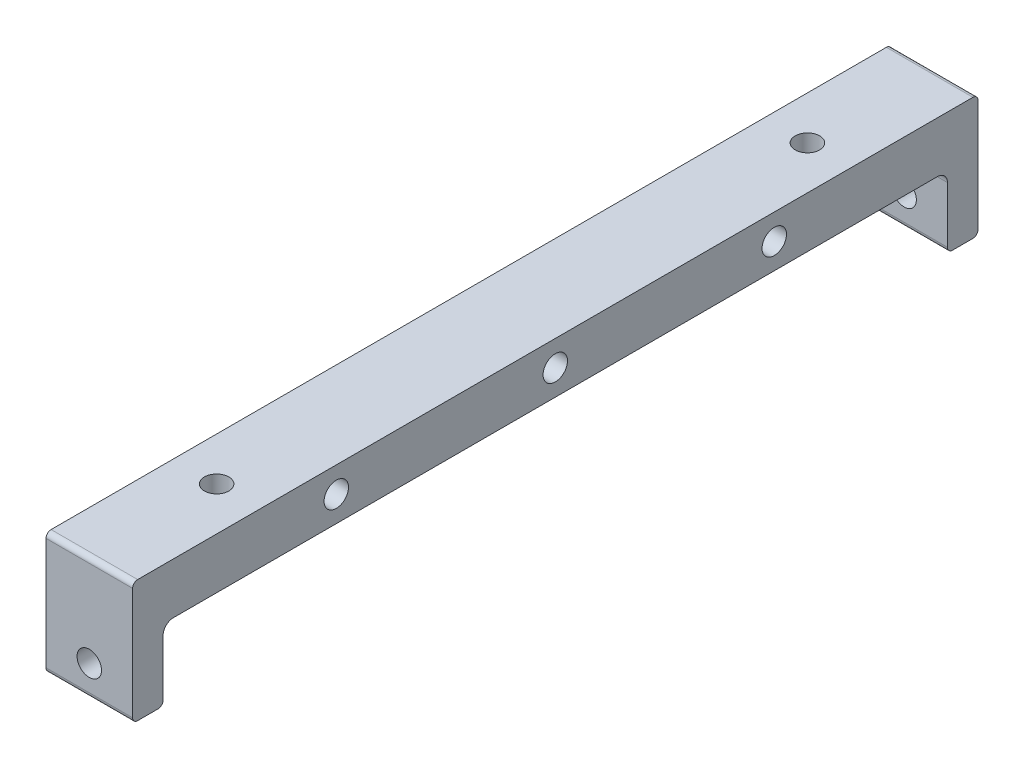
SolidWorks part; units mm, degrees
material "6061 Alloy"
ref_plane "Frontal" through (0, 0, 0) normal (0, 0, 1) x (1, 0, 0)
ref_plane "Superior" through (0, 0, 0) normal (0, 1, 0) x (1, 0, 0)
ref_plane "Direito" through (0, 0, 0) normal (1, 0, 0) x (0, 0, -1)
sketch "Sketch1" plane through (0, 0, 0) normal (0, 0, 1) x (1, 0, 0)
  line L1 (-4.25, -6) -> (4.25, -6)
  line L2 (-4.25, -6) -> (-4.25, 6)
  line L3 (-4.25, 6) -> (4.25, 6)
  line L4 (4.25, -6) -> (4.25, 6)
  line L5 (-4.25, -6) -> (4.25, 6) construction
  line L6 (-4.25, 6) -> (4.25, -6) construction
  point P0 (0, 0)
  dimension "D1" = 8.5
  dimension "D2" = 12
extrude "Boss-Extrude1" add sketch "Sketch1" along normal mid plane 83
sketch "Sketch2" plane through (4.25, 0, 0) normal (1, 0, 0) x (0, 0, -1)
  line L0 (-37.5, 1) -> (37.5, 1)
  line L1 (38.5, 0) -> (38.5, -6)
  line L2 (-41.5, -6) -> (41.5, -6) construction
  line L3 (38.5, -6) -> (-38.5, -6)
  line L4 (-38.5, -6) -> (-38.5, 0)
  line L5 (-41.5, 6) -> (41.5, 6) construction
  line L6 (-41.5, -6) -> (-41.5, 6) construction
  line L7 (41.5, -6) -> (41.5, 6) construction
  arc A0 (37.5, 1) -> (38.5, 0) centre (37.5, 0) cw
  arc A1 (-37.5, 1) -> (-38.5, 0) centre (-37.5, 0) ccw
  dimension "D4" = 1
  dimension "D5" = 1
  dimension "D1" = 5
  dimension "D2" = 3
  dimension "D3" = 3
extrude "Cut-Extrude1" cut sketch "Sketch2" against normal through all
fillet "Fillet1" radius 0.5 6 edges at (0, -6, 38.5) (0, -6, 41.5) (0, -6, -38.5) (0, -6, -41.5) (0, 6, 41.5) (0, 6, -41.5)
hole_wizard "M2 Hole1-R" positions "Sketch19" profile "Sketch18" hole size "M2" standard "DIN"
sketch "Sketch19" plane through (4.25, 0, 0) normal (1, 0, 0) x (0, 0, -1)
  line L0 (-41.5, -5.5) -> (-41.5, 5.5) construction
  line L1 (41.5, -5.5) -> (41.5, 5.5) construction
  line L2 (-41, 6) -> (41, 6) construction
  point P0 (21.5, 3.5)
  point P2 (-21.5, 3.5)
  dimension "D1" = 20
  dimension "D2" = 20
  dimension "D3" = 2.5
sketch "Sketch18" plane through (4.25, 3.5, -21.5) normal (0, 1, 0) x (0, 0, -1)
  line L0 (0, 0) -> (0, 5.721)
  line L1 (0, 5.721) -> (1.2, 5)
  line L2 (1.2, 5) -> (1.2, 0)
  line L5 (1.2, 0) -> (0, 0)
  line L10 (0, 5.721) -> (-1.2, 5) construction
  line L11 (0, -6.35) -> (0, 107.95) construction
  dimension "Hole Dia." = 2.4
  dimension "Hole Depth" = 5
  dimension "Drill Angle" = 118
hole_wizard "M2 Hole2-T" positions "Sketch13" profile "Sketch12" hole size "M2" standard "DIN"
sketch "Sketch13" plane through (4.25, 0, 0) normal (1, 0, 0) x (0, 0, -1)
  line L0 (-41, 6) -> (41, 6) construction
  point P0 (0, 3.5)
  dimension "D1" = 2.5
sketch "Sketch12" plane through (4.25, 3.5, 0) normal (0, 1, 0) x (0, 0, -1)
  line L0 (0, 0) -> (0, 4.721)
  line L1 (0, 4.721) -> (1.2, 4)
  line L2 (1.2, 4) -> (1.2, 0)
  line L5 (1.2, 0) -> (0, 0)
  line L10 (0, 4.721) -> (-1.2, 4) construction
  line L11 (0, -6.35) -> (0, 107.95) construction
  dimension "Hole Dia." = 2.4
  dimension "Hole Depth" = 4
  dimension "Drill Angle" = 118
hole_wizard "M2 Hole3-U" positions "Sketch8" profile "Sketch7" hole size "M2" standard "DIN"
sketch "Sketch8" plane through (0, 0, 41.5) normal (0, 0, 1) x (1, 0, 0)
  line L0 (4.25, -6) -> (-4.25, -6) construction
  point P0 (0, -3)
  dimension "D1" = 3
sketch "Sketch7" plane through (0, -3, 41.5) normal (1, 0, 0) x (0, -1, 0)
  line L0 (0, 0) -> (0, 10.721)
  line L1 (0, 10.721) -> (1.2, 10)
  line L2 (1.2, 10) -> (1.2, 0)
  line L5 (1.2, 0) -> (0, 0)
  line L10 (0, 10.721) -> (-1.2, 10) construction
  line L11 (0, -6.35) -> (0, 107.95) construction
  dimension "Hole Dia." = 2.4
  dimension "Hole Depth" = 10
  dimension "Drill Angle" = 118
hole_wizard "M2 Hole4-V" positions "Sketch15" profile "Sketch14" hole size "M2" standard "DIN" end condition through all
sketch "Sketch15" plane through (0, 6, 0) normal (0, 1, 0) x (1, 0, 0)
  line L0 (4.25, -41) -> (4.25, 41) construction
  line L1 (-4.25, 41.5) -> (4.25, 41.5) construction
  line L2 (4.25, -41.5) -> (-4.25, -41.5) construction
  point P0 (0, 29)
  point P2 (0, -29)
  dimension "D1" = 4.25
  dimension "D2" = 12.5
  dimension "D3" = 12.5
sketch "Sketch14" plane through (0, 6, -29) normal (1, 0, 0) x (0, 0, 1)
  line L0 (0, 0) -> (0, 12)
  line L1 (0, 12) -> (1.2, 12)
  line L2 (1.2, 12) -> (1.2, 0)
  line L5 (1.2, 0) -> (0, 0)
  line L11 (0, -6.35) -> (0, 107.95) construction
  dimension "Thru Hole Dia." = 2.4
  dimension "Thru Hole Depth" = 12
hole_wizard "M2 Hole5-W" positions "Sketch10" profile "Sketch9" hole size "M2" standard "DIN"
sketch "Sketch10" plane through (-4.25, 0, 0) normal (-1, 0, 0) x (0, 0, 1)
  line L0 (41, 6) -> (-41, 6) construction
  line L1 (41.5, 5.5) -> (41.5, -5.5) construction
  line L2 (-41.5, 5.5) -> (-41.5, -5.5) construction
  point P0 (-35.5, 3.5)
  point P2 (35.5, 3.5)
  dimension "D1" = 2.5
  dimension "D2" = 6
  dimension "D3" = 6
sketch "Sketch9" plane through (-4.25, 3.5, -35.5) normal (0, 1, 0) x (0, 0, 1)
  line L0 (0, 0) -> (0, 5.721)
  line L1 (0, 5.721) -> (1.2, 5)
  line L2 (1.2, 5) -> (1.2, 0)
  line L5 (1.2, 0) -> (0, 0)
  line L10 (0, 5.721) -> (-1.2, 5) construction
  line L11 (0, -6.35) -> (0, 107.95) construction
  dimension "Hole Dia." = 2.4
  dimension "Hole Depth" = 5
  dimension "Drill Angle" = 118
hole_wizard "M2 Hole6-Y" positions "Sketch17" profile "Sketch16" hole size "M2" standard "DIN"
sketch "Sketch17" plane through (0, 0, -41.5) normal (0, 0, -1) x (-1, 0, 0)
  line L0 (4.25, 5.5) -> (4.25, -5.5) construction
  line L1 (-4.25, 6) -> (4.25, 6) construction
  point P0 (0, -3)
  dimension "D1" = 4.25
  dimension "D2" = 9
sketch "Sketch16" plane through (0, -3, -41.5) normal (1, 0, 0) x (0, 1, 0)
  line L0 (0, 0) -> (0, 10.721)
  line L1 (0, 10.721) -> (1.2, 10)
  line L2 (1.2, 10) -> (1.2, 0)
  line L5 (1.2, 0) -> (0, 0)
  line L10 (0, 10.721) -> (-1.2, 10) construction
  line L11 (0, -6.35) -> (0, 107.95) construction
  dimension "Hole Dia." = 2.4
  dimension "Hole Depth" = 10
  dimension "Drill Angle" = 118
